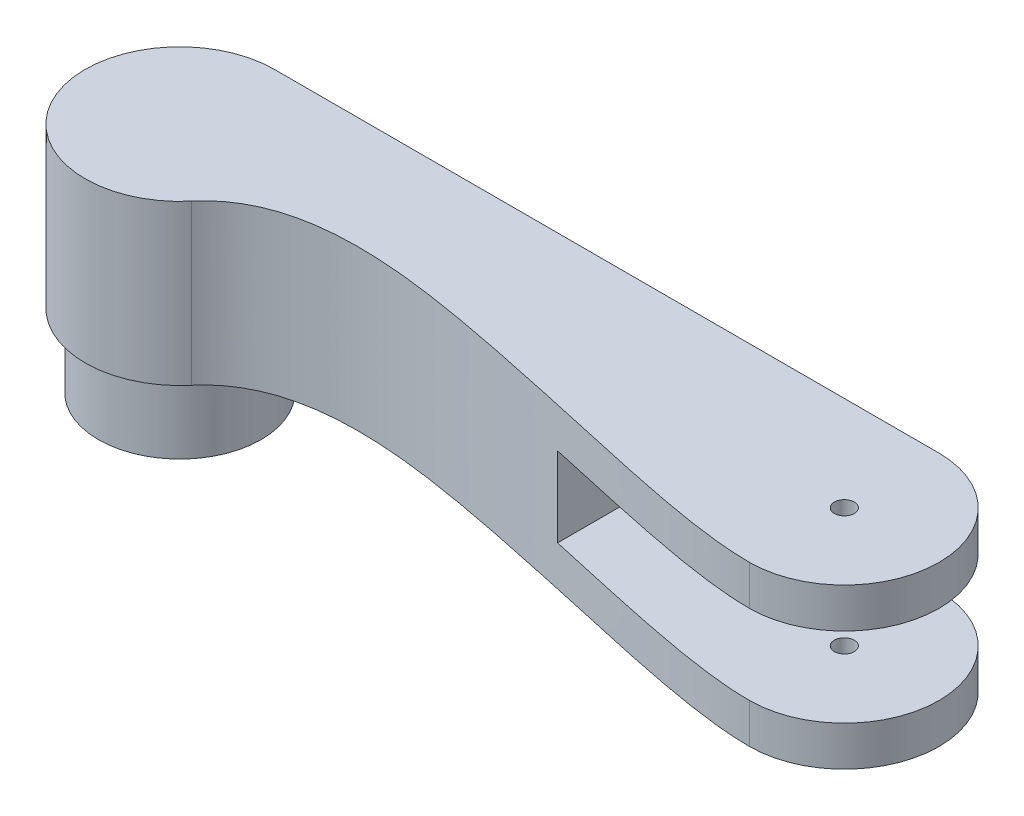
SolidWorks part; units mm, degrees
ref_plane "Front Plane" through (0, 0, 0) normal (0, 0, 1) x (1, 0, 0)
ref_plane "Top Plane" through (0, 0, 0) normal (0, 1, 0) x (1, 0, 0)
ref_plane "Right Plane" through (0, 0, 0) normal (1, 0, 0) x (0, 0, -1)
sketch "Sketch1" plane through (0, 0, 0) normal (0, 1, 0) x (1, 0, 0)
  line L0 (-50, 0) -> (50, 0) construction
  line L1 (-50, 14.25) -> (50, 14.25)
  line L2 (-50, -14.25) -> (50, -14.25)
  arc A0 (-50, 14.25) -> (-50, -14.25) centre (-50, 0) ccw
  arc A1 (50, -14.25) -> (50, 14.25) centre (50, 0) ccw
  point P3 (0, 0)
  dimension "D1" = 14.25
  dimension "D2" = 100
extrude "Boss-Extrude1" add sketch "Sketch1" along normal blind 6
sketch "Sketch3" plane through (0, 0, 0) normal (0, -1, 0) x (1, 0, 0)
  circle A0 centre (50, 0) radius 1.5
  dimension "D1" = 3
extrude "Cut-Extrude2" cut sketch "Sketch3" against normal through all
sketch "Sketch4" plane through (0, 6, 0) normal (0, 1, 0) x (1, 0, 0)
  line L0 (-50, 14.25) -> (15, 14.25)
  line L1 (-50, 14.25) -> (50, 14.25) construction
  line L2 (15, 14.25) -> (15, -14.25)
  line L3 (-50, -14.25) -> (50, -14.25) construction
  line L4 (15, -14.25) -> (-50, -14.25)
  arc A0 (-50, 14.25) -> (-50, -14.25) centre (-50, 0) ccw
  arc A1 (-50, 14.25) -> (-50, -14.25) centre (-50, 0) ccw construction
  dimension "D1" = 65
extrude "Boss-Extrude2" add sketch "Sketch4" along normal blind 12
sketch "Sketch5" plane through (0, 18, 0) normal (0, 1, 0) x (1, 0, 0)
  line L0 (-50, 0) -> (50, 0) construction
  line L1 (-50, 14.25) -> (50, 14.25)
  line L2 (-50, -14.25) -> (50, -14.25)
  arc A0 (-50, 14.25) -> (-50, -14.25) centre (-50, 0) ccw
  arc A1 (50, -14.25) -> (50, 14.25) centre (50, 0) ccw
  point P4 (0, 0)
  dimension "D1" = 14.25
extrude "Boss-Extrude3" add sketch "Sketch5" along normal blind 6
sketch "Sketch6" plane through (0, 24, 0) normal (0, 1, 0) x (1, 0, 0)
  circle A0 centre (50, 0) radius 1.5
  dimension "D1" = 3
extrude "Cut-Extrude3" cut sketch "Sketch6" against normal up to next
sketch "Sketch7" plane through (0, 24, 0) normal (0, 1, 0) x (1, 0, 0)
  line L0 (0, -13.2) -> (0, 13.2) construction
  line L1 (-50, -14.25) -> (50, -14.25)
  circle A0 centre (-50, 0) radius 14.25
  circle A1 centre (50, 0) radius 14.25
  spline S0 degree 3 poles (-39.0732, -9.1469) (-31.5141, -0.117) (5.4387, -4.6452) (38.6975, -14.25) (50, -14.25) knots 0 0 0 0 0.435908 1 1 1 1
  line M5 (-50, -14.25) -> (50, -14.25)
extrude "Cut-Extrude4" cut sketch "Sketch7" against normal up to next contours S0 A0 M5
sketch "Sketch8" plane through (0, 0, 0) normal (0, -1, 0) x (1, 0, 0)
  circle A1 centre (-50, 0) radius 12.25
  dimension "D1" = 24.5
extrude "Boss-Extrude4" add sketch "Sketch8" along normal blind 11
sketch "Sketch9" plane through (0, -11, 0) normal (0, -1, 0) x (1, 0, 0)
  circle A0 centre (-50, 0) radius 7.5 construction
  circle A1 centre (-50, 7.5) radius 2.5
  circle A2 centre (-50, -7.5) radius 2.5
  arc A3 (-50, 14.25) -> (-50, -14.25) centre (-50, 0) ccw construction
  circle A4 centre (-50, 0) radius 3
  point P6 (-50, 0)
  dimension "D1" = 15
  dimension "D2" = 5
  dimension "D3" = 6
extrude "Cut-Extrude5" cut sketch "Sketch9" against normal blind 6
equation "\"Length\"= 100mm"
equation "\"Radius\"= 14.25mm"
equation "\"Thick\"= 12mm"
equation "\"D1@Sketch1\"= \"Radius\""
equation "\"D2@Sketch1\" = \"Length\""
equation "\"D1@Boss-Extrude1\"= \"Thick\""
equation "\"D1@Sketch4\"=\"Length\"*0.65"
equation "\"D1@Sketch5\"=\"Radius\""
equation "\"D1@Boss-Extrude2\"=\"Thick\""
equation "\"D1@Boss-Extrude4\"=\"Thick\"-1"
